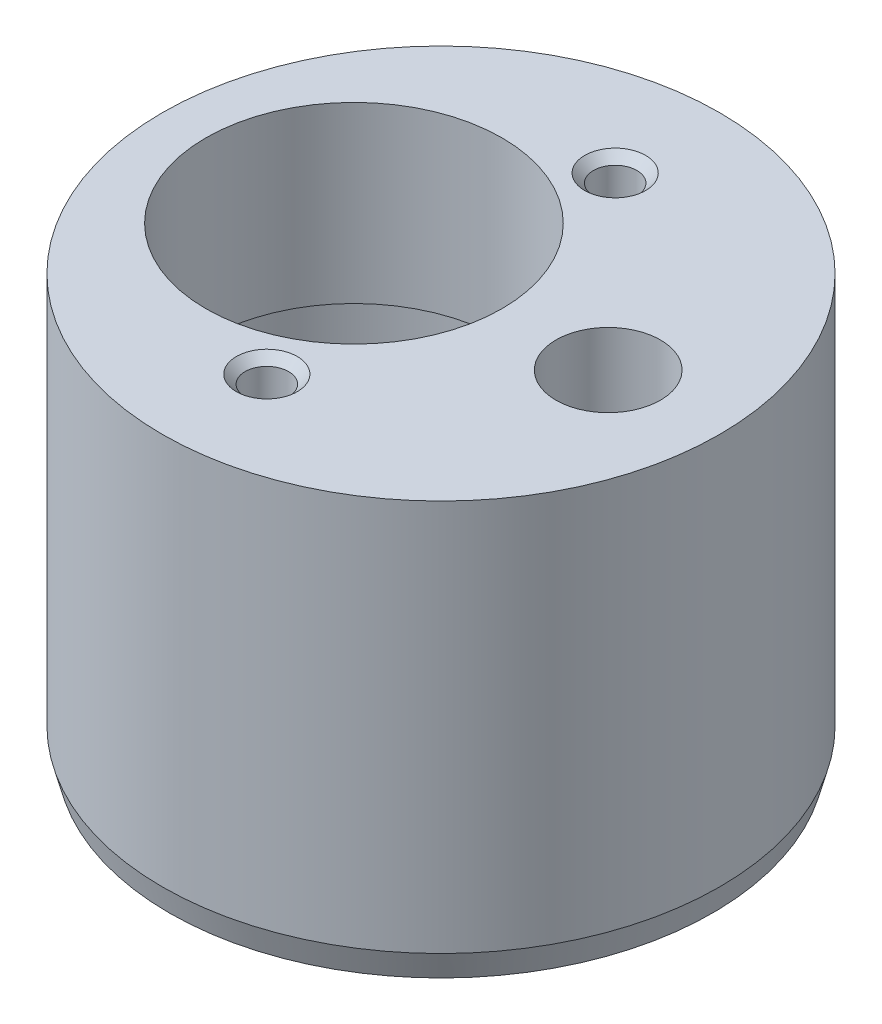
SolidWorks part; units mm, degrees
material "2024 Сплав"
ref_plane "Спереди" through (0, 0, 0) normal (0, 0, 1) x (1, 0, 0)
ref_plane "Сверху" through (0, 0, 0) normal (0, 1, 0) x (1, 0, 0)
ref_plane "Справа" through (0, 0, 0) normal (1, 0, 0) x (0, 0, -1)
sketch "Эскиз1" plane through (0, 0, 0) normal (0, 1, 0) x (1, 0, 0)
  circle A0 centre (0, 0) radius 16
  dimension "D1" = 32
extrude "Бобышка-Вытянуть1" add sketch "Эскиз1" along normal blind 24
sketch "Эскиз2" plane through (0, 24, 0) normal (0, 1, 0) x (1, 0, 0)
  circle A0 centre (-5, 0) radius 8.5
  dimension "D1" = 17
  dimension "D2" = 5
extrude "Вырез-Вытянуть1" cut sketch "Эскиз2" against normal blind 14
sketch "Эскиз3" plane through (0, 24, 0) normal (0, 1, 0) x (1, 0, 0)
  circle A0 centre (9.6, 0) radius 3
  dimension "D1" = 6
  dimension "D2" = 9.6
extrude "Вырез-Вытянуть2" cut sketch "Эскиз3" against normal blind 20
sketch "Эскиз4" plane through (0, 0, 0) normal (0, 1, 0) x (1, 0, 0)
  circle A0 centre (-5, 0) radius 9.5
  dimension "D1" = 19
extrude "Вырез-Вытянуть4" cut sketch "Эскиз4" along normal blind 14
chamfer "Фаска1" distance 0.5 angle 60 1 edges at (-5, 0, 9.5)
chamfer "Фаска2" distance 1.5 angle 15 1 edges at (0, 0, 16)
sketch "Эскиз15" plane through (0, 24, 0) normal (0, 1, 0) x (1, 0, 0)
  line L0 (0, -10) -> (0, 10) construction
  point P4 (0, 0)
  dimension "D2" = 20
hole_wizard "Отверстие обработанное метчиком M3x0.51" positions "Эскиз18" profile "Эскиз19" tap size "M3x0.5" standard "Ansi Metric"
sketch "Эскиз18" plane through (0, 24, 0) normal (0, 1, 0) x (1, 0, 0)
  point P0 (0, 10)
  point P3 (0, -10)
sketch "Эскиз19" plane through (0, 24, -10) normal (1, 0, 0) x (0, 0, 1)
  line L0 (0, 0) -> (0, 6.2511)
  line L1 (0, 6.2511) -> (1.25, 5.5)
  line L2 (1.25, 5.5) -> (1.25, 0)
  line L5 (1.25, 0) -> (0, 0)
  line L10 (0, 6.2511) -> (-1.25, 5.5) construction
  line L11 (0, -6.35) -> (0, 107.95) construction
  dimension "Диаметр сверла" = 2.5
  dimension "Глубина сверла" = 5.5
  dimension "Угол заточки сверла" = 118
cosmetic thread "Отверстие резьбы1" parameters "D1"=4, "D2"=3
cosmetic thread "Отверстие резьбы2" parameters "D1"=4, "D2"=3
chamfer "Фаска3" distance 0.5 angle 45 2 edges at (0, 24, 11.25) (0, 24, -8.75)
